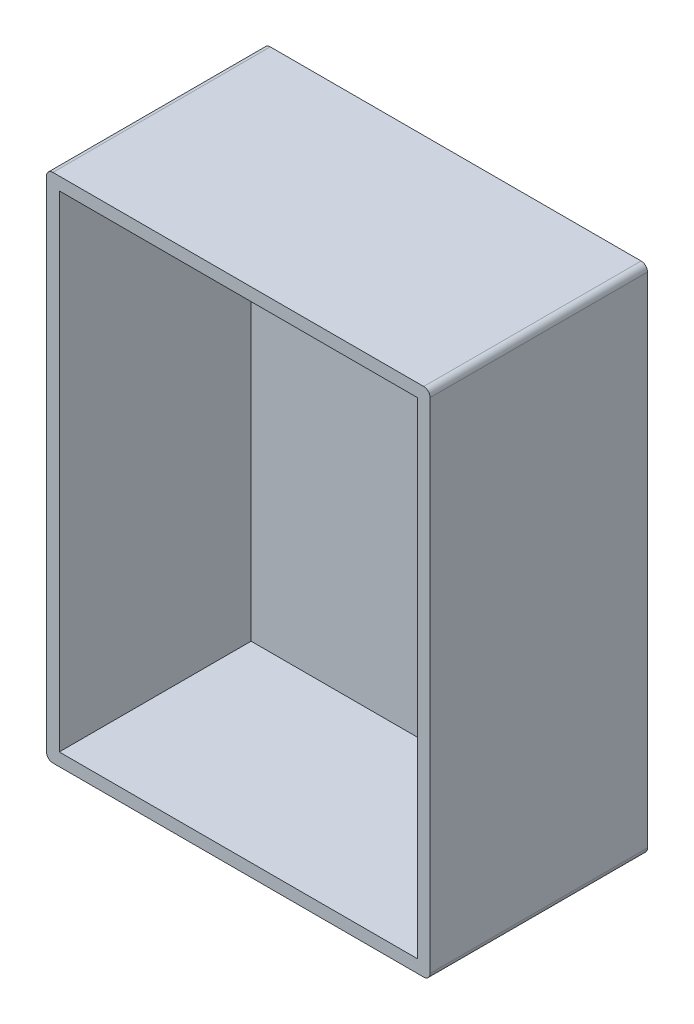
SolidWorks part; units mm, degrees
ref_plane "前视基准面" through (0, 0, 0) normal (0, 0, 1) x (1, 0, 0)
ref_plane "上视基准面" through (0, 0, 0) normal (0, 1, 0) x (1, 0, 0)
ref_plane "右视基准面" through (0, 0, 0) normal (1, 0, 0) x (0, 0, -1)
sketch "草图1" plane through (0, 0, 0) normal (0, 0, 1) x (1, 0, 0)
  line L0 (0, 200) -> (0, -200) construction
  line L1 (150, 200) -> (-150, 200)
  line L2 (150, 200) -> (150, -200)
  line L3 (150, -200) -> (-150, -200)
  line L4 (-150, 200) -> (-150, -200)
  line L5 (150, 0) -> (-150, 0) construction
  point P8 (0, 0)
  dimension "D1" = 300
  dimension "D2" = 400
extrude "凸台-拉伸1" add sketch "草图1" along normal blind 170
sketch "草图2" plane through (0, 0, 170) normal (0, 0, 1) x (1, 0, 0)
  line L0 (0, -190) -> (0, 190) construction
  line L1 (-140, 190) -> (140, 190)
  line L2 (-140, 190) -> (-140, -190)
  line L3 (-140, -190) -> (140, -190)
  line L4 (140, 190) -> (140, -190)
  line L5 (140, 0) -> (-140, 0) construction
  point P8 (0, 0)
  dimension "D1" = 280
  dimension "D2" = 380
extrude "切除-拉伸1" cut sketch "草图2" against normal blind 150
sketch "草图3" plane through (0, 0, 0) normal (0, 0, 1) x (1, 0, 0)
  line L0 (150, 0) -> (-150, 0) construction
  line L1 (150, -200) -> (150, 200) construction
  line L2 (-150, 200) -> (-150, -200) construction
  line L3 (0, 200) -> (0, -200) construction
  line L4 (150, 200) -> (-150, 200) construction
  line L5 (-150, -200) -> (150, -200) construction
  point P12 (0, 0)
fillet "圆角1" radius 5 4 edges at (-150, 200, 85) (150, 200, 85) (150, -200, 85) (-150, -200, 85)
